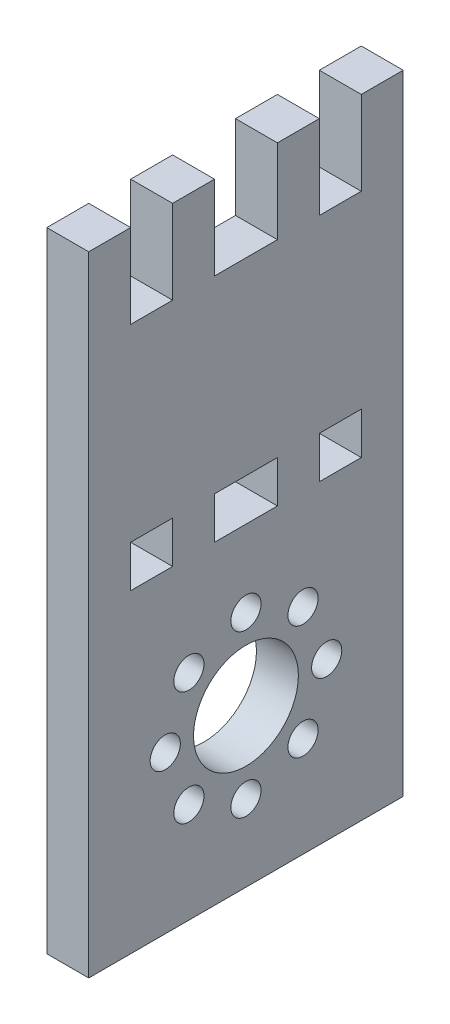
SolidWorks part; units mm, degrees
ref_plane "Front Plane" through (0, 0, 0) normal (0, 0, 1) x (1, 0, 0)
ref_plane "Top Plane" through (0, 0, 0) normal (0, 1, 0) x (1, 0, 0)
ref_plane "Right Plane" through (0, 0, 0) normal (1, 0, 0) x (0, 0, -1)
sketch "Sketch1" plane through (0, 0, 0) normal (1, 0, 0) x (0, 0, -1)
  line L0 (-38.1, -28.1371) -> (0, -28.1371) construction
  line L1 (-38.1, 29.0129) -> (0, 29.0129)
  line L2 (-38.1, 29.0129) -> (-38.1, -47.1871)
  line L3 (-38.1, -47.1871) -> (0, -47.1871)
  line L4 (0, 29.0129) -> (0, -47.1871)
  line L5 (-19.05, 29.0129) -> (-19.05, -47.1871) construction
  circle A0 centre (-19.05, -18.3581) radius 1.8288
  circle A1 centre (-19.05, -28.1371) radius 6.35
  circle A2 centre (-12.1352, -21.2223) radius 1.8288
  circle A3 centre (-9.271, -28.1371) radius 1.8288
  circle A4 centre (-12.1352, -35.0519) radius 1.8288
  circle A5 centre (-19.05, -37.9161) radius 1.8288
  circle A6 centre (-25.9648, -35.0519) radius 1.8288
  circle A7 centre (-28.829, -28.1371) radius 1.8288
  circle A8 centre (-25.9648, -21.2223) radius 1.8288
  point P8 (-19.05, -28.1371)
  point P30 (-19.05, -28.1371)
  dimension "D4" = 3.6576
  dimension "D6" = 12.7
  dimension "D1" = 76.2
  dimension "D2" = 38.1
  dimension "D3" = 19.05
  dimension "D5" = 9.779
  dimension "D7" = 8
extrude "Boss-Extrude1" add sketch "Sketch1" along normal blind 5.08
sketch "Sketch2" plane through (5.08, 0, 0) normal (1, 0, 0) x (0, 0, -1)
  line L0 (-38.1, 18.8529) -> (0, 18.8529) construction
  line L1 (-38.1, 29.0129) -> (-38.1, -47.1871) construction
  line L2 (0, -47.1871) -> (0, 29.0129) construction
  line L3 (-38.1, -9.0871) -> (0, -9.0871) construction
  line L4 (-38.1, -47.1871) -> (0, -47.1871) construction
  line L5 (-38.1, -4.0071) -> (0, -4.0071) construction
  line L6 (0, 29.0129) -> (-38.1, 29.0129) construction
  line L8 (-33.02, 29.0129) -> (-27.94, 29.0129)
  line L10 (-33.02, 29.0129) -> (-33.02, 18.8529)
  line L11 (-33.02, 18.8529) -> (-27.94, 18.8529)
  line L12 (-27.94, 29.0129) -> (-27.94, 18.8529)
  line L14 (-10.16, 29.0129) -> (-5.08, 29.0129)
  line L15 (-10.16, 29.0129) -> (-10.16, 18.8529)
  line L16 (-10.16, 18.8529) -> (-5.08, 18.8529)
  line L18 (-5.08, 29.0129) -> (-5.08, 18.8529)
  line L19 (-22.86, 29.0129) -> (-15.24, 29.0129)
  line L20 (-22.86, 29.0129) -> (-22.86, 18.8529)
  line L22 (-22.86, 18.8529) -> (-15.24, 18.8529)
  line L24 (-33.02, -4.0071) -> (-27.94, -4.0071)
  line L25 (-33.02, -4.0071) -> (-33.02, -9.0871)
  line L26 (-33.02, -9.0871) -> (-27.94, -9.0871)
  line L28 (-27.94, -4.0071) -> (-27.94, -9.0871)
  line L29 (-22.86, -4.0071) -> (-15.24, -4.0071)
  line L30 (-22.86, -4.0071) -> (-22.86, -9.0871)
  line L32 (-22.86, -9.0871) -> (-15.24, -9.0871)
  line L33 (-15.24, -4.0071) -> (-15.24, -9.0871)
  line L34 (-10.16, -4.0071) -> (-5.08, -4.0071)
  line L36 (-10.16, -4.0071) -> (-10.16, -9.0871)
  line L37 (-10.16, -9.0871) -> (-5.08, -9.0871)
  line L38 (-5.08, -4.0071) -> (-5.08, -9.0871)
  line L39 (-15.24, 29.0129) -> (-15.24, 18.8529)
  dimension "D1" = 38.1
  dimension "D2" = 10.16
  dimension "D3" = 5.08
  dimension "D4" = 5.08
  dimension "D5" = 5.08
  dimension "D6" = 5.08
  dimension "D7" = 5.08
  dimension "D8" = 5.08
  dimension "D9" = 5.08
  dimension "D10" = 5.08
  dimension "D11" = 5.08
  dimension "D12" = 5.08
  dimension "D13" = 5.08
  dimension "D14" = 5.08
  dimension "D15" = 5.08
extrude "Cut-Extrude1" cut sketch "Sketch2" against normal blind 5.08
sketch "Sketch3" plane through (5.08, 0, 0) normal (1, 0, 0) x (0, 0, -1)
  line L0 (-19.05, -47.1871) -> (-19.05, 18.8529)
  line L3 (-38.1, -47.1871) -> (0, -47.1871) construction
  line L4 (-22.86, 18.8529) -> (-15.24, 18.8529) construction
